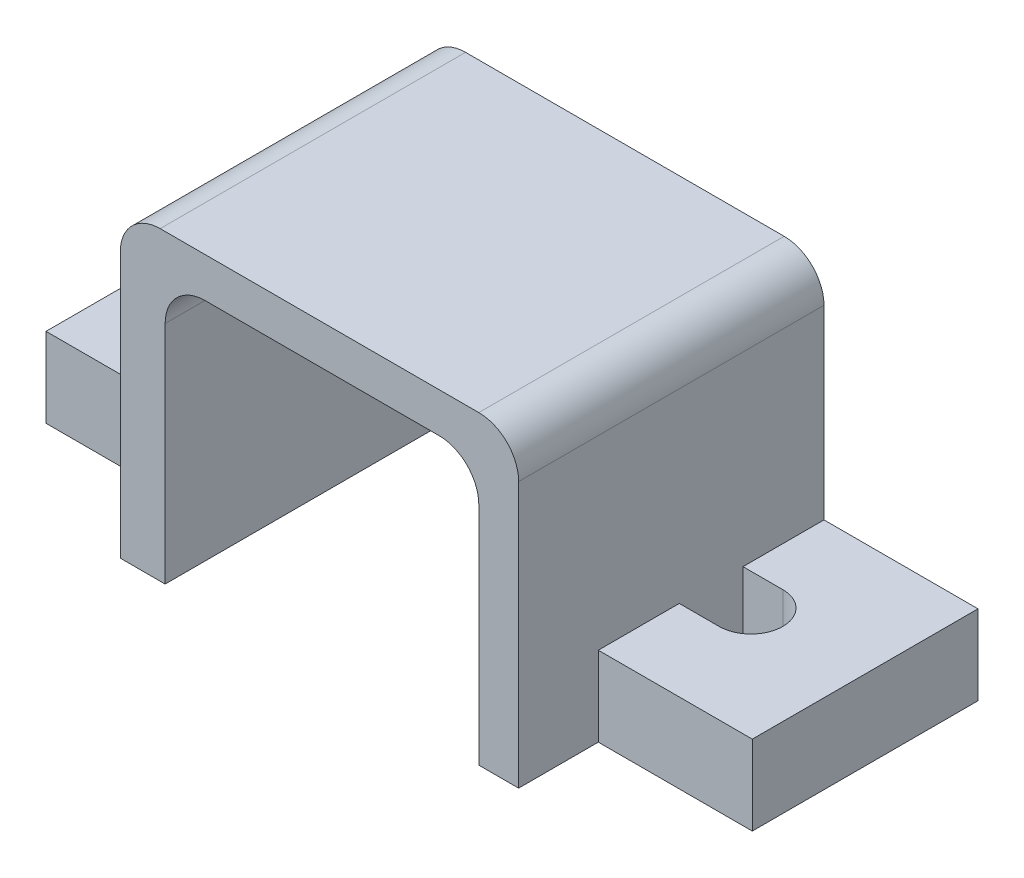
SolidWorks part; units mm, degrees
material "ABS"
ref_plane "正面" through (0, 0, 0) normal (0, 0, 1) x (1, 0, 0)
ref_plane "平面" through (0, 0, 0) normal (0, 1, 0) x (1, 0, 0)
ref_plane "右側面" through (0, 0, 0) normal (1, 0, 0) x (0, 0, -1)
sketch "ｽｹｯﾁ1" plane through (0, 0, 0) normal (0, 0, 1) x (1, 0, 0)
  line L0 (0, 0) -> (7.5, 0)
  line L1 (55, 0) -> (-55, 0) construction
  line L2 (7.5, 0) -> (7.5, 11.5)
  line L3 (7.5, 11.5) -> (-7.5, 11.5)
  line L4 (-7.5, 11.5) -> (-7.5, 0)
  line L5 (-7.5, 0) -> (0, 0)
extrude "ﾎﾞｽ - 押し出し1" add sketch "ｽｹｯﾁ1" along normal blind 11.5
sketch "ｽｹｯﾁ3" plane through (0, 0, 0) normal (0, 0, 1) x (1, 0, 0)
  line L0 (-7.3125, 0) -> (-5.8125, 0) construction
  line L1 (6.325, 0) -> (-6.325, 0) construction
  line L2 (-5.8125, 0) -> (-5.8125, 10) construction
  line L3 (-5.8125, 10) -> (6, 10) construction
  line L4 (6, 10) -> (6, 0) construction
  line L5 (6, 0) -> (7.5, 0) construction
  line L6 (7.5, 0) -> (7.5, 11.5) construction
  line L8 (6, 0) -> (-5.8125, 0)
  line L9 (6, 0) -> (6, 10)
  line L10 (6, 10) -> (-5.8125, 10)
  line L11 (-5.8125, 0) -> (-5.8125, 10)
extrude "ｶｯﾄ - 押し出し1" cut sketch "ｽｹｯﾁ3" along normal blind 11.5
fillet "ﾌｨﾚｯﾄ1" radius 1.5 1 edges at (6, 10, 5.75)
fillet "ﾌｨﾚｯﾄ2" radius 1.5 1 edges at (-5.8125, 10, 5.75)
fillet "ﾌｨﾚｯﾄ3" radius 1.5 1 edges at (7.5, 11.5, 5.75)
fillet "ﾌｨﾚｯﾄ4" radius 1.5 1 edges at (-7.5, 11.5, 5.75)
sketch "ｽｹｯﾁ5" plane through (0, 0, 0) normal (0, 1, 0) x (1, 0, 0)
  line L0 (-7.5, 0) -> (-13.3, 0)
  line L1 (-6.325, 0) -> (6.325, 0) construction
  line L2 (-13.3, 0) -> (-13.3, -8.5)
  line L3 (-13.3, -8.5) -> (-7.5, -8.5)
  line L4 (-7.5, -11.5) -> (-7.5, 0) construction
  line L5 (-7.5, -8.5) -> (-7.5, 0)
  line L6 (7.5, 0) -> (13.3, 0)
  line L7 (13.3, 0) -> (13.3, -8.5)
  line L8 (13.3, -8.5) -> (7.5, -8.5)
  line L9 (7.5, -11.5) -> (7.5, 0) construction
  line L10 (7.5, -8.5) -> (7.5, 0)
extrude "ﾎﾞｽ - 押し出し2" add sketch "ｽｹｯﾁ5" along normal blind 3
sketch "ｽｹｯﾁ6" plane through (0, 0, 0) normal (0, 1, 0) x (1, 0, 0)
  line L0 (13.3, -4.25) -> (-13.3, -4.25) construction
  line L1 (13.3, -8.5) -> (13.3, 0) construction
  line L2 (-13.3, 0) -> (-13.3, -8.5) construction
  line L3 (0, -4.25) -> (-9, -4.25) construction
  line L4 (0, -4.25) -> (9, -4.25) construction
hole_wizard "M2 すきま穴1" positions "ｽｹｯﾁ8" profile "ｽｹｯﾁ7" hole size "M2" standard "JIS" end condition through all
sketch "ｽｹｯﾁ8" plane through (0, 0, 0) normal (0, -1, 0) x (-1, 0, 0)
  point P0 (9, -4.25)
  point P3 (-9, -4.25)
sketch "ｽｹｯﾁ7" plane through (-9, 0, 4.25) normal (1, 0, 0) x (0, 0, -1)
  line L0 (0, 0) -> (0, 11.5)
  line L1 (0, 11.5) -> (1.2, 11.5)
  line L2 (1.2, 11.5) -> (1.2, 0)
  line L5 (1.2, 0) -> (0, 0)
  line L11 (0, -6.35) -> (0, 107.95) construction
  dimension "通し穴の直径" = 2.4
  dimension "通し穴の深さ" = 11.5
sketch "ｽｹｯﾁ9" plane through (0, 0, 0) normal (0, 1, 0) x (1, 0, 0)
  line L0 (9, -4.25) -> (9, -3.05) construction
  line L1 (9, -3.05) -> (-9, -3.05) construction
  line L2 (-9, -3.05) -> (-9, -5.45) construction
  line L3 (-9, -5.45) -> (9, -5.45) construction
  line L4 (9, -5.45) -> (9, -4.25) construction
  line L5 (9, -5.45) -> (7.5, -5.45)
  line L6 (7.5, -5.45) -> (7.5, -3.05)
  line L7 (7.5, -3.05) -> (9, -3.05)
  line L8 (9, -3.05) -> (9, -5.45)
  line L9 (-9, -3.05) -> (-9, -5.45)
  line L10 (-9, -5.45) -> (-7.5, -5.45)
  line L11 (-7.5, -5.45) -> (-7.5, -3.05)
  line L12 (-7.5, -3.05) -> (-9, -3.05)
  circle A0 centre (9, -4.25) radius 1.2 construction
  circle A1 centre (-9, -4.25) radius 1.2 construction
extrude "ｶｯﾄ - 押し出し4" cut sketch "ｽｹｯﾁ9" along normal blind 3
